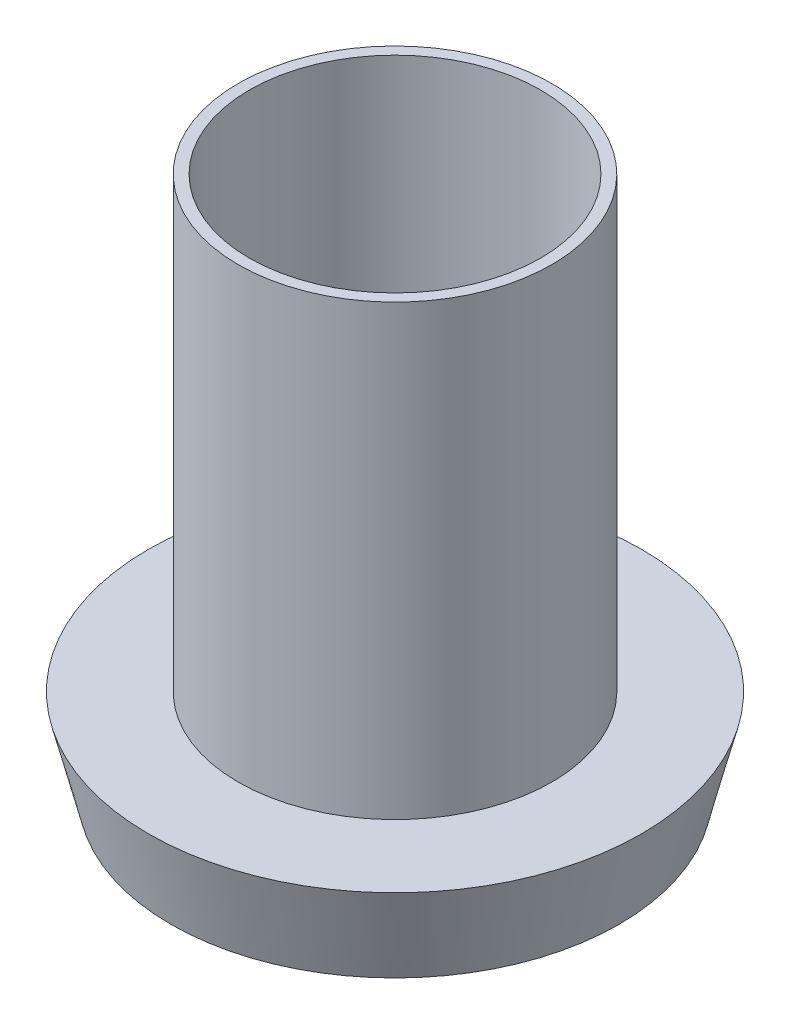
SolidWorks part; units mm, degrees
ref_plane "Front Plane" through (0, 0, 0) normal (0, 0, 1) x (1, 0, 0)
ref_plane "Top Plane" through (0, 0, 0) normal (0, 1, 0) x (1, 0, 0)
ref_plane "Right Plane" through (0, 0, 0) normal (1, 0, 0) x (0, 0, -1)
sketch "Sketch1" plane through (0, 0, 0) normal (0, 1, 0) x (1, 0, 0)
  circle A0 centre (0, 0) radius 5.5
  dimension "D1" = 11
ref_plane "Plane1" through (0, -2, 0) normal (0, 1, 0) x (1, 0, 0)
sketch "Sketch2" plane through (0, -2, 0) normal (0, 1, 0) x (1, 0, 0)
  circle A0 centre (0, 0) radius 5
  dimension "D1" = 10
loft "Loft1" add profiles "Sketch2", "Sketch1"
sketch "Sketch3" plane through (0, 0, 0) normal (0, 1, 0) x (1, 0, 0)
  circle A0 centre (0, 0) radius 0.5
  dimension "D1" = 1
extrude "Cut-Extrude1" cut sketch "Sketch3" against normal through all
sketch "Sketch4" plane through (0, 0, 0) normal (0, 1, 0) x (1, 0, 0)
  circle A0 centre (0, 0) radius 3.5
  circle A1 centre (0, 0) radius 3.25
  dimension "D1" = 7
  dimension "D2" = 6.5
extrude "Boss-Extrude1" add sketch "Sketch4" along normal blind 10
sketch "Sketch5" plane through (0, 0, 0) normal (0, 1, 0) x (1, 0, 0)
  circle A0 centre (0, 0) radius 0.75
  circle A1 centre (0, 0) radius 0.25
  dimension "D1" = 0.5
  dimension "D2" = 1.5
extrude "Boss-Extrude2" add sketch "Sketch5" along normal blind 2
